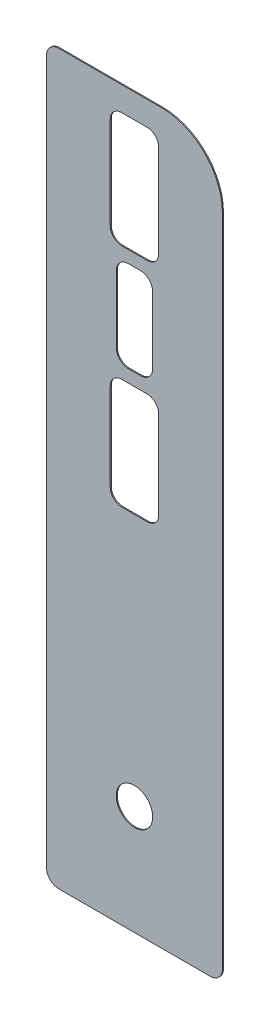
SolidWorks part; units mm, degrees
material "3M 9474LE (300LSE)"
ref_plane "Front Plane" through (0, 0, 0) normal (0, 0, 1) x (1, 0, 0)
ref_plane "Top Plane" through (0, 0, 0) normal (0, 1, 0) x (1, 0, 0)
ref_plane "Right Plane" through (0, 0, 0) normal (1, 0, 0) x (0, 0, -1)
other "Configuration Table"
sketch "Sketch7" plane through (0, 0, 0) normal (0, 0, 1) x (1, 0, 0)
  line L0 (0, 60) -> (0, -60) construction
  line L1 (-12.5, 60) -> (4.5, 60)
  line L2 (-14.5, 58) -> (-14.5, -58)
  line L3 (-12.5, -60) -> (12.5, -60)
  line L4 (14.5, 50) -> (14.5, -58)
  line L5 (-14.5, 60) -> (14.5, -60) construction
  line L6 (-14.5, -60) -> (14.5, 60) construction
  line L7 (-14.5, 0) -> (14.5, 0) construction
  line L8 (0, -0.121) -> (0, 0.121) construction
  arc A0 (-14.5, -58) -> (-12.5, -60) centre (-12.5, -58) ccw
  arc A1 (12.5, -60) -> (14.5, -58) centre (12.5, -58) ccw
  arc A2 (4.5, 60) -> (14.5, 50) centre (4.5, 50) cw
  arc A3 (-12.5, 60) -> (-14.5, 58) centre (-12.5, 58) ccw
  point P0 (0, 0)
extrude "Boss-Extrude5" add sketch "Sketch7" along normal blind 0.17
sketch "Sketch1"
  line L40 (-2.1, -0.3) -> (2.1, -0.3) construction
  line L86 (-4, 16.0318) -> (-4, 1.6) construction
  line L89 (4, 1.6) -> (4, 16.0318) construction
  line L94 (2.1, 17.9318) -> (-2.1, 17.9318) construction
  line L95 (2.1, 56) -> (-2.1, 56) construction
  line L96 (4, 38.9) -> (4, 54.1) construction
  line L101 (-2.1, 37) -> (2.1, 37) construction
  line L106 (-4, 54.1) -> (-4, 38.9) construction
  line L107 (-2.1, -0.3) -> (2.1, -0.3)
  line L114 (-4, 16.0318) -> (-4, 1.6)
  line L135 (4, 1.6) -> (4, 16.0318)
  line L136 (2.1, 17.9318) -> (-2.1, 17.9318)
  line L137 (2.1, 56) -> (-2.1, 56)
  line L138 (4, 38.9) -> (4, 54.1)
  line L139 (-2.1, 37) -> (2.1, 37)
  line L140 (-4, 54.1) -> (-4, 38.9)
  line L141 (0, -42) -> (0, -60) construction
  line L142 (-12.5, -60) -> (12.5, -60) construction
  circle A55 centre (0, -42) radius 3
  arc A109 (2.1, -0.3) -> (4, 1.6) centre (2.1, 1.6) ccw construction
  arc A112 (-4, 1.6) -> (-2.1, -0.3) centre (-2.1, 1.6) ccw construction
  arc A113 (-2.1, 17.9318) -> (-4, 16.0318) centre (-2.1, 16.0318) ccw construction
  arc A114 (4, 16.0318) -> (2.1, 17.9318) centre (2.1, 16.0318) ccw construction
  arc A115 (2.1, 37) -> (4, 38.9) centre (2.1, 38.9) ccw construction
  arc A116 (4, 54.1) -> (2.1, 56) centre (2.1, 54.1) ccw construction
  arc A117 (-2.1, 56) -> (-4, 54.1) centre (-2.1, 54.1) ccw construction
  arc A118 (-4, 38.9) -> (-2.1, 37) centre (-2.1, 38.9) ccw construction
  arc A119 (2.1, -0.3) -> (4, 1.6) centre (2.1, 1.6) ccw
  arc A120 (-4, 1.6) -> (-2.1, -0.3) centre (-2.1, 1.6) ccw
  arc A121 (-2.1, 17.9318) -> (-4, 16.0318) centre (-2.1, 16.0318) ccw
  arc A122 (4, 16.0318) -> (2.1, 17.9318) centre (2.1, 16.0318) ccw
  arc A123 (2.1, 37) -> (4, 38.9) centre (2.1, 38.9) ccw
  arc A124 (4, 54.1) -> (2.1, 56) centre (2.1, 54.1) ccw
  arc A125 (-2.1, 56) -> (-4, 54.1) centre (-2.1, 54.1) ccw
  arc A126 (-4, 38.9) -> (-2.1, 37) centre (-2.1, 38.9) ccw
  dimension "D1" = 6
  dimension "D2" = 18
extrude "Cut-Extrude1" cut sketch "Sketch1" against normal through all
sketch "Sketch8" plane through (0, 0, 0.17) normal (0, 0, 1) x (1, 0, 0)
  line L8 (-3, 33) -> (-3, 22) construction
  line L9 (-1, 20) -> (1, 20) construction
  line L10 (3, 22) -> (3, 33) construction
  line L11 (1, 35) -> (-1, 35) construction
  line L12 (-3, 33) -> (-3, 22)
  line L13 (-1, 20) -> (1, 20)
  line L14 (3, 22) -> (3, 33)
  line L15 (1, 35) -> (-1, 35)
  arc A8 (-3, 22) -> (-1, 20) centre (-1, 22) ccw construction
  arc A9 (1, 20) -> (3, 22) centre (1, 22) ccw construction
  arc A10 (3, 33) -> (1, 35) centre (1, 33) ccw construction
  arc A11 (-1, 35) -> (-3, 33) centre (-1, 33) ccw construction
  arc A12 (-3, 22) -> (-1, 20) centre (-1, 22) ccw
  arc A13 (1, 20) -> (3, 22) centre (1, 22) ccw
  arc A14 (3, 33) -> (1, 35) centre (1, 33) ccw
  arc A15 (-1, 35) -> (-3, 33) centre (-1, 33) ccw
extrude "Cut-Extrude2" cut sketch "Sketch8" against normal through all
